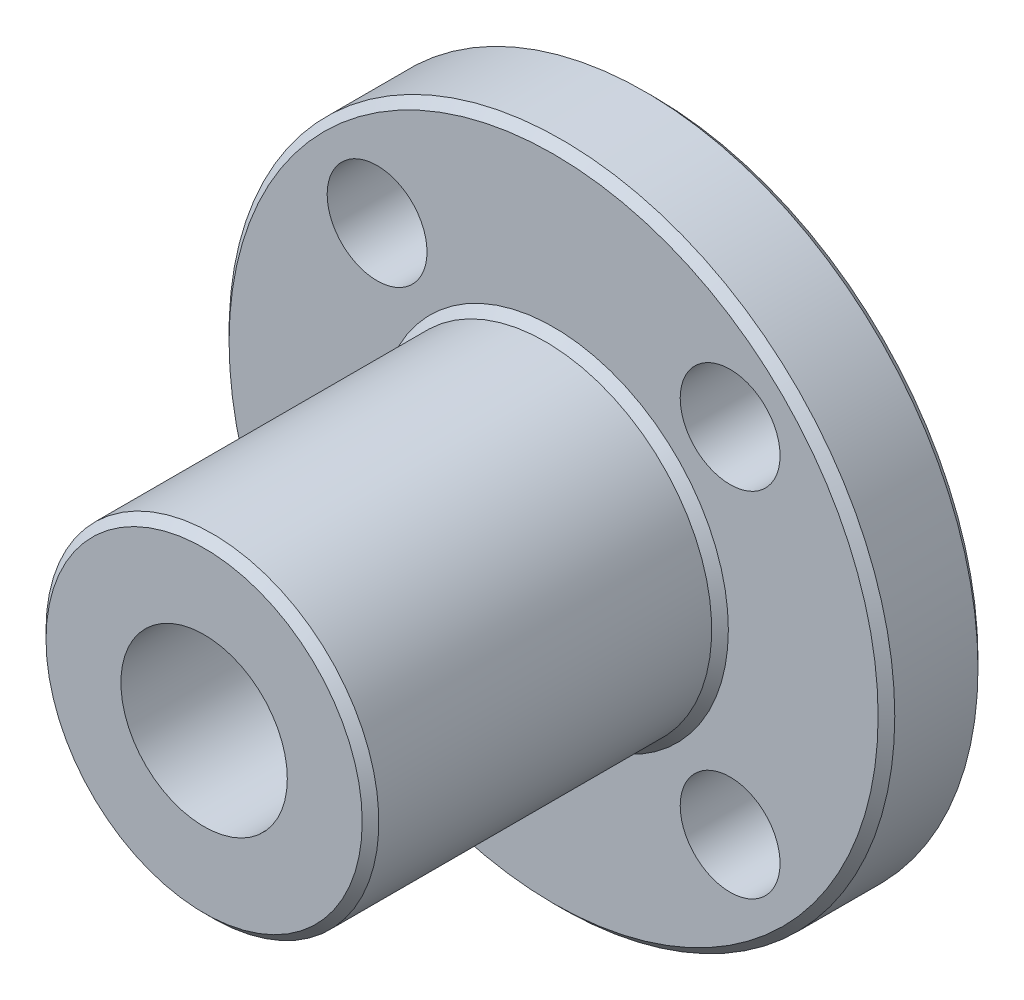
SolidWorks part; units mm, degrees
ref_plane "Front Plane" through (0, 0, 0) normal (0, 0, 1) x (1, 0, 0)
ref_plane "Top Plane" through (0, 0, 0) normal (0, 1, 0) x (1, 0, 0)
ref_plane "Right Plane" through (0, 0, 0) normal (1, 0, 0) x (0, 0, -1)
sketch "Sketch1" plane through (0, 0, 0) normal (0, 0, 1) x (1, 0, 0)
  circle A0 centre (0, 0) radius 10
  dimension "D1" = 20
extrude "Boss-Extrude1" add sketch "Sketch1" along normal blind 3
sketch "Sketch2" plane through (0, 0, 3) normal (0, 0, 1) x (1, 0, 0)
  circle A0 centre (0, 0) radius 5
  dimension "D1" = 10
extrude "Boss-Extrude2" add sketch "Sketch2" along normal blind 10.5
sketch "Sketch3" plane through (0, 0, 13.5) normal (0, 0, 1) x (1, 0, 0)
  circle A0 centre (0, 0) radius 2.5
  dimension "D1" = 5
extrude "Cut-Extrude1" cut sketch "Sketch3" against normal through all both
chamfer "Chamfer1" distance 0.25 angle 45 4 edges at (5, 0, 13.5) (10, 0, 0) (10, 0, 3) (5, 0, 3)
sketch "Sketch4" plane through (0, 0, 0) normal (0, 0, -1) x (-1, 0, 0)
  line L0 (-5.3033, 5.3033) -> (0, 0) construction
  line L1 (0, 0) -> (0, 7.5) construction
  circle A0 centre (0, 0) radius 7.5 construction
  circle A1 centre (-5.3033, 5.3033) radius 1.5
  circle A2 centre (5.3033, 5.3033) radius 1.5
  circle A3 centre (5.3033, -5.3033) radius 1.5
  circle A4 centre (-5.3033, -5.3033) radius 1.5
  point P15 (0, 0)
  dimension "D1" = 15
  dimension "D2" = 3
  dimension "D3" = 45
  dimension "D4" = 4
extrude "Cut-Extrude2" cut sketch "Sketch4" against normal through all both
